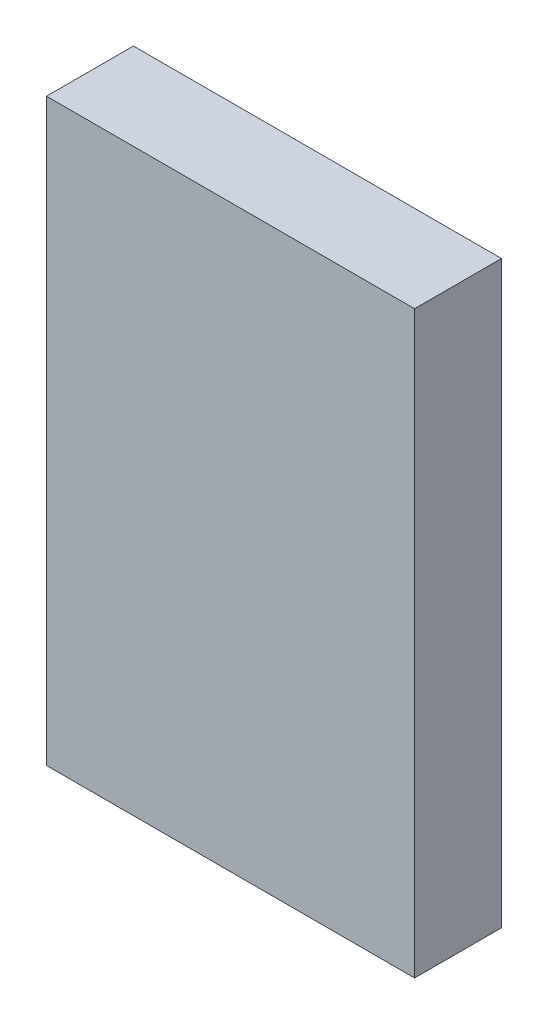
SolidWorks part; units mm, degrees
material "ABS"
ref_plane "前基準面" through (0, 0, 0) normal (0, 0, 1) x (1, 0, 0)
ref_plane "上基準面" through (0, 0, 0) normal (0, 1, 0) x (1, 0, 0)
ref_plane "右基準面" through (0, 0, 0) normal (1, 0, 0) x (0, 0, -1)
sketch "草圖1" plane through (0, 0, 0) normal (0, 0, 1) x (1, 0, 0)
  line L0 (0, 0) -> (10.3578, 0) construction
  line L1 (-6.35, 10) -> (6.35, 10)
  line L2 (-6.35, 10) -> (-6.35, -10)
  line L3 (-6.35, -10) -> (6.35, -10)
  line L4 (6.35, 10) -> (6.35, -10)
  line L5 (0, 0) -> (0, 11.5259) construction
  dimension "D1" = 20
  dimension "D2" = 12.7
extrude "填料-伸長1" add sketch "草圖1" along normal blind 3
